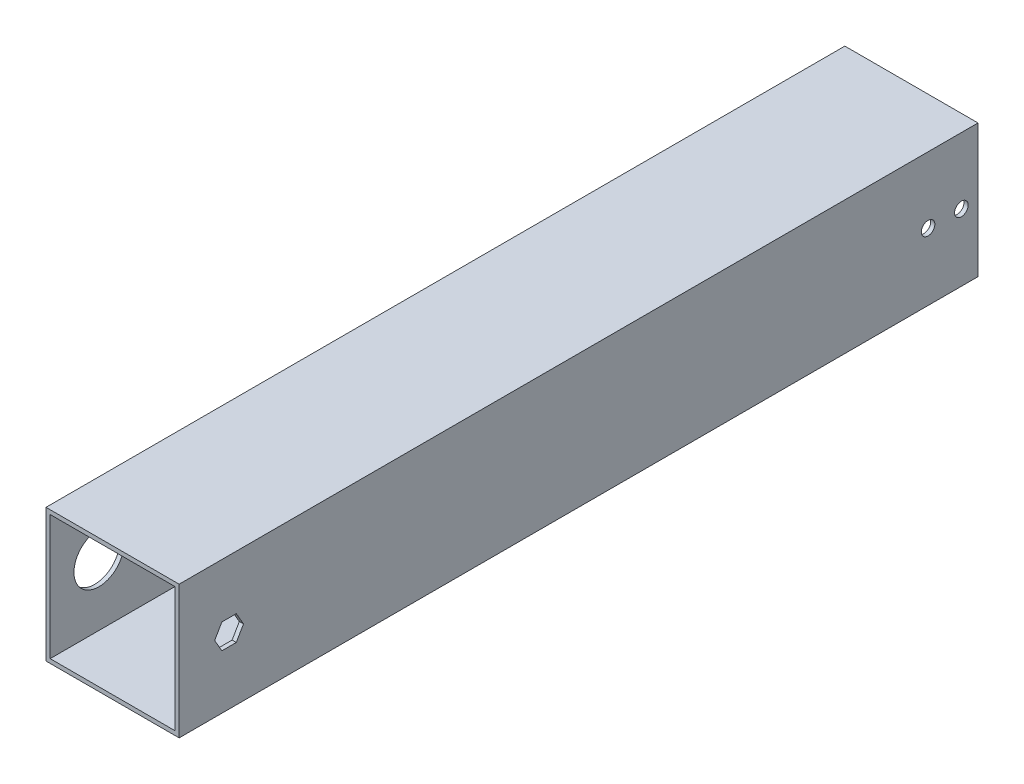
SolidWorks part; units mm, degrees
ref_plane "Front Plane" through (0, 0, 0) normal (0, 0, 1) x (1, 0, 0)
ref_plane "Top Plane" through (0, 0, 0) normal (0, 1, 0) x (1, 0, 0)
ref_plane "Right Plane" through (0, 0, 0) normal (1, 0, 0) x (0, 0, -1)
sketch "Sketch1" plane through (0, 0, 0) normal (0, 0, 1) x (1, 0, 0)
  line L1 (-29.3367, 25.2382) -> (21.4633, 25.2382)
  line L2 (-29.3367, 25.2382) -> (-29.3367, -25.5618)
  line L3 (-29.3367, -25.5618) -> (21.4633, -25.5618)
  line L4 (21.4633, 25.2382) -> (21.4633, -25.5618)
  line L5 (-27.7492, 23.6507) -> (19.8758, 23.6507)
  line L6 (-27.7492, 23.6507) -> (-27.7492, -23.9743)
  line L7 (-27.7492, -23.9743) -> (19.8758, -23.9743)
  line L8 (19.8758, 23.6507) -> (19.8758, -23.9743)
  dimension "D1" = 50.8
  dimension "D2" = 50.8
  dimension "D3" = 1.5875
  dimension "D4" = 1.5875
  dimension "D5" = 1.5875
  dimension "D6" = 1.5875
extrude "Boss-Extrude1" add sketch "Sketch1" along normal blind 304.8
sketch "Sketch2" plane through (21.4633, 0, 0) normal (1, 0, 0) x (0, 0, -1)
  line L2 (-304.8, 25.2382) -> (0, 25.2382) construction
  line L3 (-280.2507, -0.1618) -> (-283.0004, 4.6007)
  line L4 (-283.0004, 4.6007) -> (-288.4996, 4.6007)
  line L5 (-288.4996, 4.6007) -> (-291.2493, -0.1618)
  line L6 (-291.2493, -0.1618) -> (-288.4996, -4.9243)
  line L7 (-288.4996, -4.9243) -> (-283.0004, -4.9243)
  line L8 (-283.0004, -4.9243) -> (-280.2507, -0.1618)
  line L9 (-304.8, -25.5618) -> (-304.8, 25.2382) construction
  circle A1 centre (-285.75, -0.1618) radius 4.7625 construction
  point P0 (-285.75, -0.1618)
  dimension "D1" = 9.525
  dimension "D2" = 25.4
  dimension "D3" = 19.05
extrude "Cut-Extrude1" cut sketch "Sketch2" against normal blind 304.8
sketch "Sketch3" plane through (21.4633, 0, 0) normal (1, 0, 0) x (0, 0, -1)
  line L0 (0, -25.5618) -> (0, 25.2382) construction
  circle A0 centre (-6.35, 0) radius 2.5797
  circle A1 centre (-19.05, 0) radius 2.5797
  dimension "D3" = 5.1594
  dimension "D4" = 5.1594
  dimension "D1" = 19.05
  dimension "D2" = 6.35
extrude "Cut-Extrude2" cut sketch "Sketch3" against normal blind 159
sketch "Sketch4" plane through (-29.3367, 0, 0) normal (-1, 0, 0) x (0, 0, 1)
  circle A0 centre (286.1907, 0) radius 9.525
  dimension "D1" = 19.05
extrude "Cut-Extrude3" cut sketch "Sketch4" against normal blind 3.175
